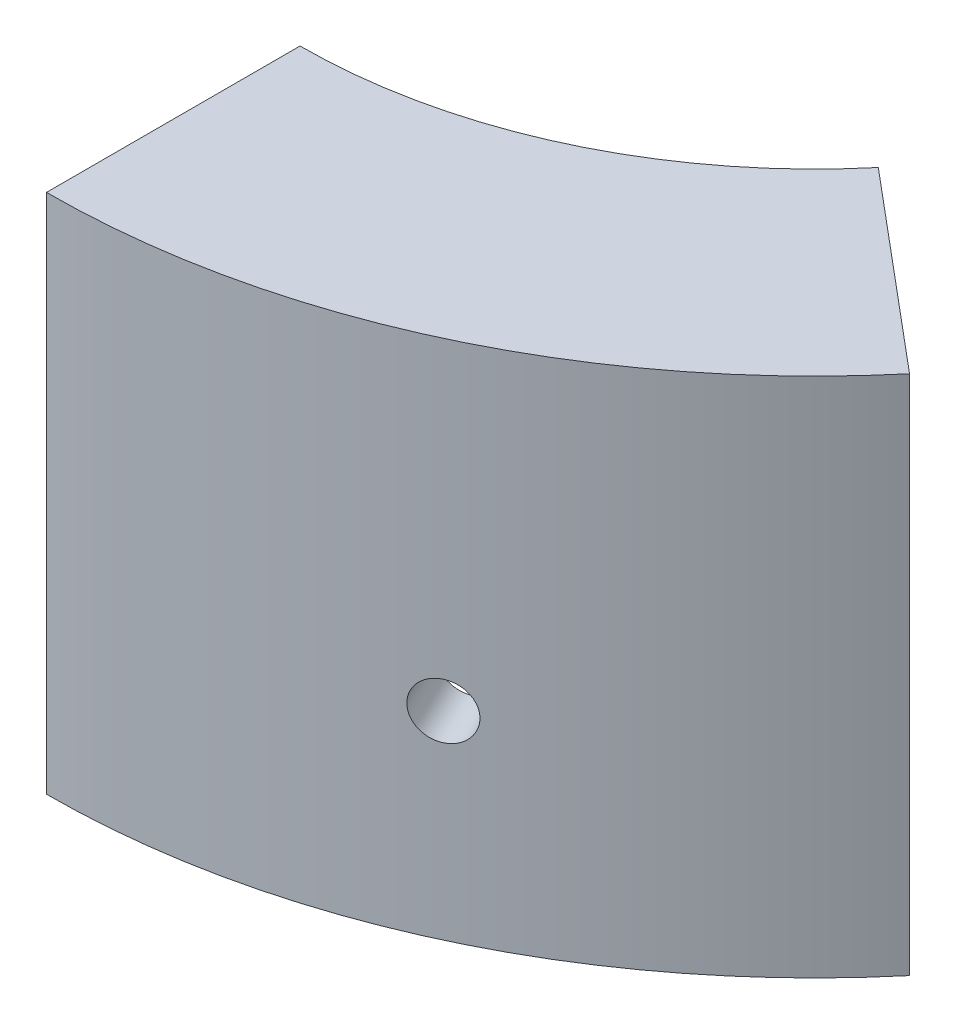
SolidWorks part; units mm, degrees
ref_plane "Front Plane" through (0, 0, 0) normal (0, 0, 1) x (1, 0, 0)
ref_plane "Top Plane" through (0, 0, 0) normal (0, 1, 0) x (1, 0, 0)
ref_plane "Right Plane" through (0, 0, 0) normal (1, 0, 0) x (0, 0, -1)
sketch "Sketch1" plane through (0, 0, 0) normal (0, 1, 0) x (1, 0, 0)
  line L0 (0, -43.2) -> (0, -46.8)
  line L1 (33.0931, -27.7684) -> (35.8509, -30.0825)
  circle A0 centre (0, 0) radius 46.8
  circle A1 centre (0, 0) radius 43.2
  dimension "D1" = 93.6
  dimension "D3" = 50
  dimension "D2" = 3.6
extrude "Boss-Extrude1" add sketch "Sketch1" along normal blind 6.25 contours A1 L0 A0 L1
sketch "Sketch2" plane through (0, 6.25, 0) normal (0, 1, 0) x (1, 0, 0)
  line L0 (0, -40.2) -> (0, -60)
  line L1 (45.9627, -38.5673) -> (30.795, -25.8401)
  line L2 (33.0931, -27.7684) -> (35.8509, -30.0825) construction
  circle A0 centre (0, 0) radius 60
  circle A1 centre (0, 0) radius 40.2
  arc M4 (33.0931, -27.7684) -> (0, -43.2) centre (0, 0) cw
  line M5 (0, -43.2) -> (0, -46.8)
  arc M6 (0, -46.8) -> (35.8509, -30.0825) centre (0, 0) ccw
  line M7 (35.8509, -30.0825) -> (33.0931, -27.7684)
  dimension "D1" = 120
  dimension "D2" = 80.4
extrude "Boss-Extrude2" add sketch "Sketch2" along normal blind 5 contours L0 A0 L1 M6 | M7 M4 M5 M6 | A1 L0 L1 M4
sketch "Sketch3" plane through (0, 6.25, 0) normal (0, -1, 0) x (-1, 0, 0)
  arc A2 (-42.2857, -35.4819) -> (0, -55.2) centre (0, 0) ccw
  arc A3 (-42.2857, -35.4819) -> (0, -55.2) centre (0, 0) ccw
  line M2 (0, -60) -> (0, -46.8)
  line M4 (-35.8509, -30.0825) -> (-45.9627, -38.5673)
  arc M5 (-45.9627, -38.5673) -> (0, -60) centre (0, 0) ccw
  dimension "D1" = 4.8
extrude "Boss-Extrude3" add sketch "Sketch3" along normal blind 35.7 contours A3 M4 M5 M2
ref_plane "Plane1" through (15.3975, 0, 33.02) normal (0.4226, 0, 0.9063) x (0.9063, 0, -0.4226)
sketch "Sketch4" plane through (15.3975, 0, 33.02) normal (0.4226, 0, 0.9063) x (0.9063, 0, -0.4226)
  line L0 (-25.3571, -29.45) -> (25.3571, -29.45) construction
  circle A0 centre (0, -13.95) radius 2.15
  dimension "D1" = 4.3
  dimension "D2" = 15.5
extrude "M4-through hole" cut sketch "Sketch4" along normal through all
